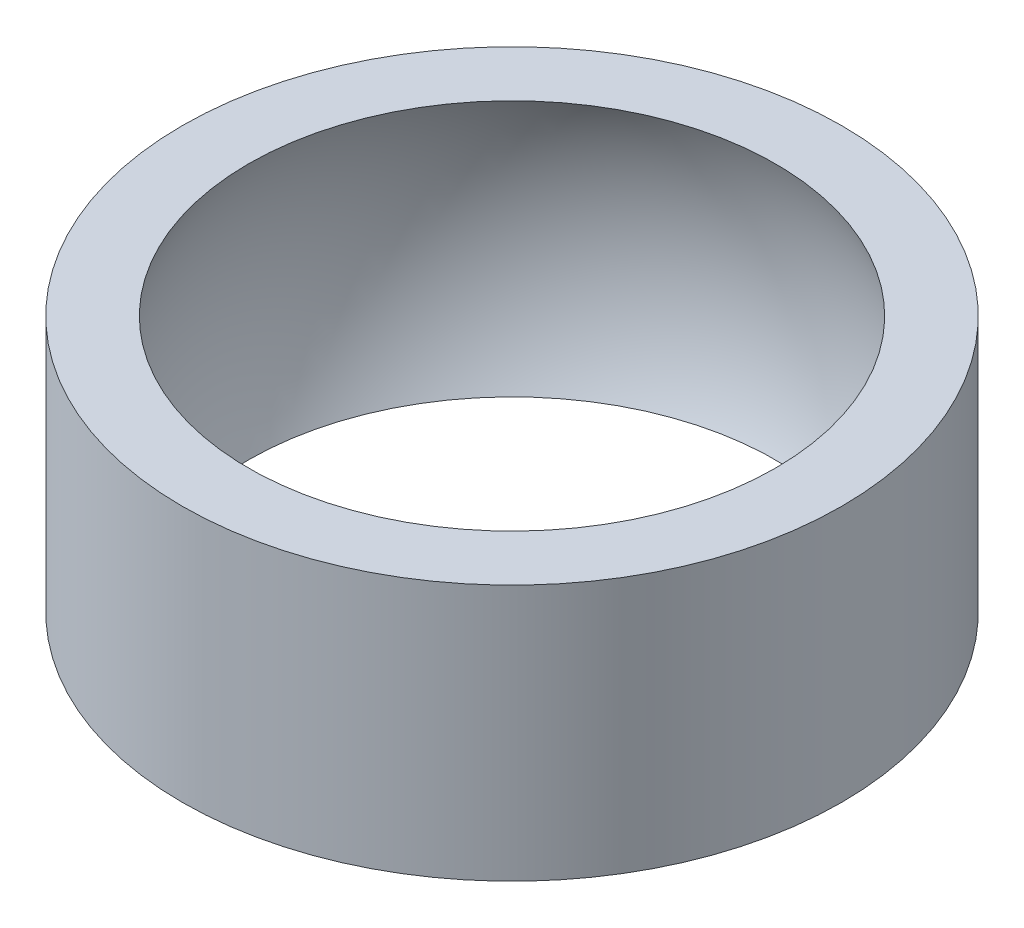
SolidWorks part; units mm, degrees
ref_plane "Plan de face" through (0, 0, 0) normal (0, 0, 1) x (1, 0, 0)
ref_plane "Plan de dessus" through (0, 0, 0) normal (0, 1, 0) x (1, 0, 0)
ref_plane "Plan de droite" through (0, 0, 0) normal (1, 0, 0) x (0, 0, -1)
sketch "Esquisse1" plane through (0, 0, 0) normal (0, 0, 1) x (1, 0, 0)
  line L0 (0, 2.5636) -> (0, -3.2461) construction
  line L1 (-3.5969, 1.75) -> (-4.5, 1.75)
  line L2 (-3.5969, -1.75) -> (-4.5, -1.75)
  line L3 (-4.5, -1.75) -> (-4.5, 1.75)
  arc A0 (-3.5969, 1.75) -> (-3.5969, -1.75) centre (0, 0) ccw
  point P6 (-4, 0)
  dimension "D2" = 4
  dimension "D1" = 4.5
  dimension "D3" = 3.5
revolve "Révolution1" add sketch "Esquisse1" angle 360 about L0
